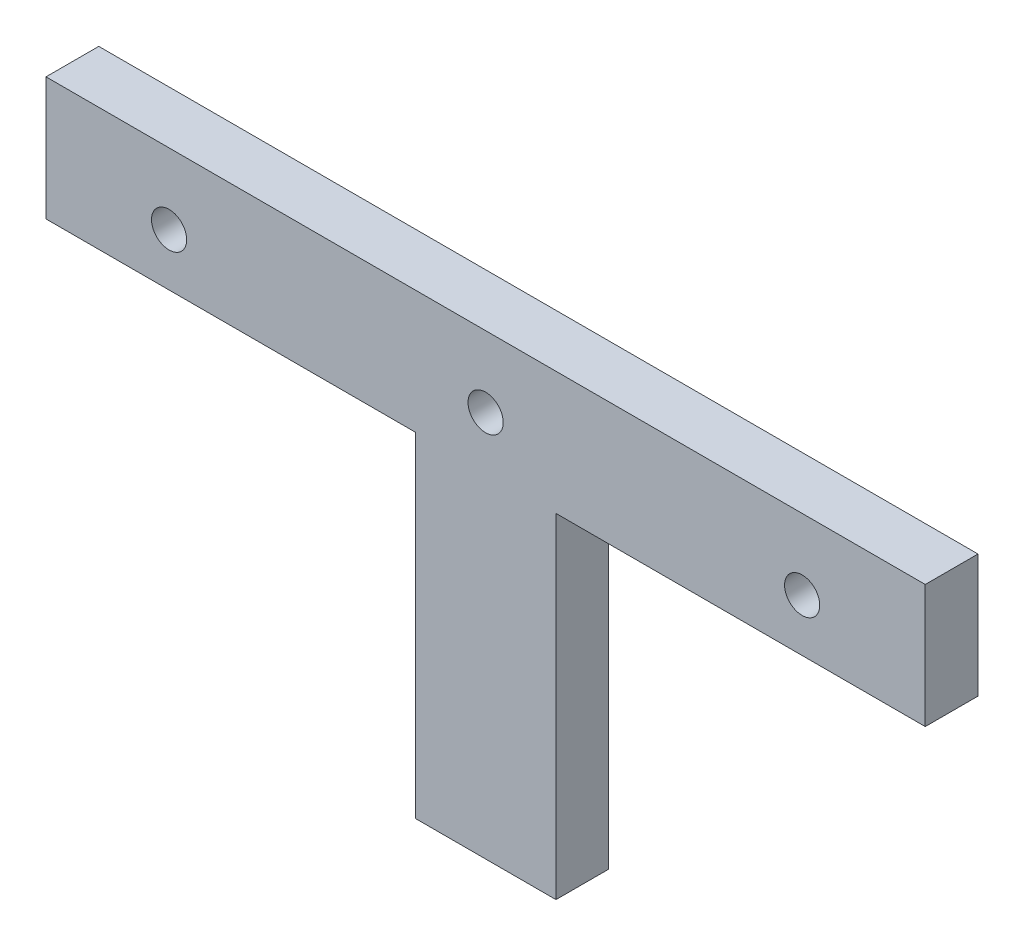
SolidWorks part; units mm, degrees
ref_plane "前基準面" through (0, 0, 0) normal (0, 0, 1) x (1, 0, 0)
ref_plane "上基準面" through (0, 0, 0) normal (0, 1, 0) x (1, 0, 0)
ref_plane "右基準面" through (0, 0, 0) normal (1, 0, 0) x (0, 0, -1)
sketch "草圖1" plane through (0, 0, 0) normal (0, 0, 1) x (1, 0, 0)
  line L0 (-15.1551, 7.2196) -> (-55.1551, 7.2196)
  line L1 (-55.1551, 7.2196) -> (-55.1551, 102.3297)
  line L2 (-55.1551, 102.3297) -> (-160.1551, 102.3297)
  line L3 (-160.1551, 102.3297) -> (-160.1551, 137.3297)
  line L4 (-160.1551, 137.3297) -> (89.8449, 137.3297)
  line L5 (89.8449, 137.3297) -> (89.8449, 102.3297)
  line L6 (89.8449, 102.3297) -> (-15.1551, 102.3297)
  line L7 (-15.1551, 102.3297) -> (-15.1551, 7.2196)
  line L8 (-35.1551, 137.3297) -> (-35.1551, 151.4898) construction
  line L9 (-35.1551, 7.2196) -> (-35.1551, -12.7977) construction
  dimension "D1" = 250
  dimension "D2" = 35
  dimension "D3" = 40
extrude "填料-伸長1" add sketch "草圖1" along normal blind 15
sketch "草圖2" plane through (0, 0, 15) normal (0, 0, 1) x (1, 0, 0)
  line L0 (89.8449, 102.3297) -> (89.8449, 137.3297) construction
  circle A0 centre (54.8449, 117.1895) radius 5
  circle A1 centre (-35.1551, 117.1895) radius 5
  circle A2 centre (-125.1551, 117.1895) radius 5
  dimension "D1" = 10
  dimension "D2" = 10
  dimension "D3" = 10
  dimension "D4" = 90
  dimension "D5" = 90
  dimension "D6" = 35
extrude "除料-伸長1" cut sketch "草圖2" against normal through all
sketch "草圖3" plane through (89.8449, 0, 0) normal (1, 0, 0) x (0, 0, -1)
  line L0 (0, 102.3297) -> (0, 137.3297) construction
  line L1 (-15, 137.3297) -> (0, 137.3297) construction
  circle A0 centre (-7.5, 131.3297) radius 4
  dimension "D1" = 8
  dimension "D2" = 7.5
  dimension "D3" = 6
